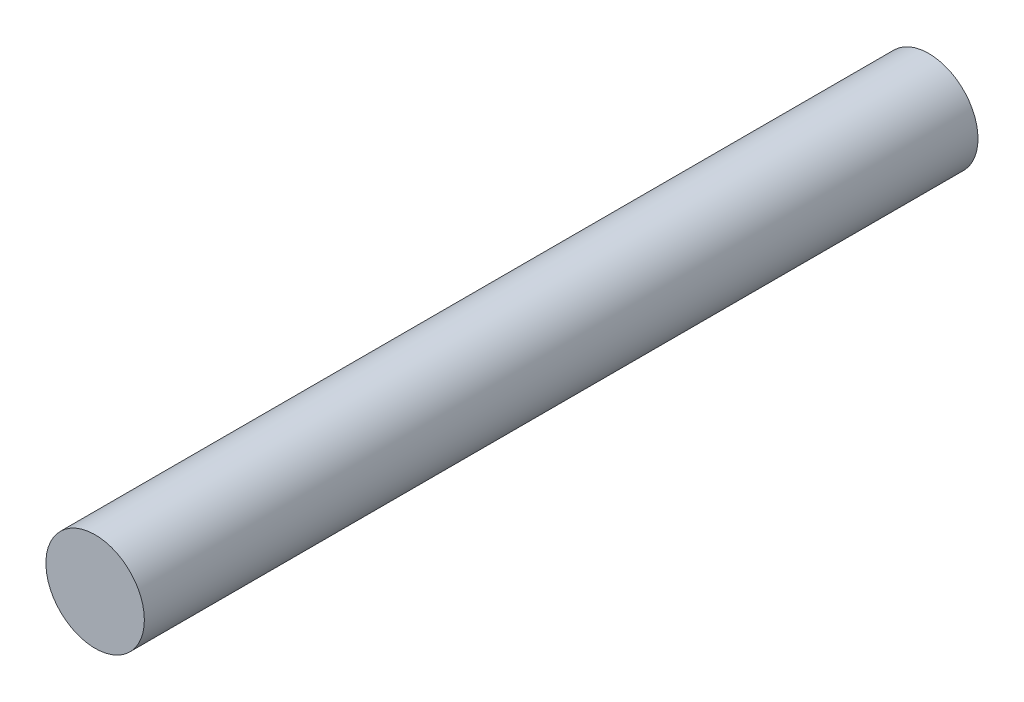
SolidWorks part; units mm, degrees
ref_plane "Front" through (0, 0, 0) normal (0, 0, 1) x (1, 0, 0)
ref_plane "Top" through (0, 0, 0) normal (0, 1, 0) x (1, 0, 0)
ref_plane "Right" through (0, 0, 0) normal (1, 0, 0) x (0, 0, -1)
sketch "Sketch1" plane through (0, 0, 0) normal (0, 0, 1) x (1, 0, 0)
  circle A0 centre (0, 0) radius 3
extrude "Boss-Extrude1" add sketch "Sketch1" along normal blind 50.8
sketch "For Drawing" plane through (0, 0, 0) normal (0, 0, 1) x (1, 0, 0)
  circle A0 centre (0, 0) radius 3
  circle A1 centre (0, 0) radius 3 construction
  dimension "Diameter" = 6
sketch "Break Point" plane through (0, 0, 0) normal (1, 0, 0) x (0, 0, -1)
  line L0 (-50.8, 0) -> (-41.8, 0)
  line L1 (-50.8, 3) -> (-50.8, -3) construction
  line L2 (0, 0) -> (-9, 0)
  line L3 (-9, -3) -> (-9, 3) construction
  line L4 (0, 3) -> (-50.8, 3) construction
  line L5 (-41.8, -3) -> (-41.8, 3) construction
  point P12 (-9, 0)
  point P15 (-41.8, 0)
  dimension "D1" = 9
equation "\"D1@Break Point\"=\"Diameter@Sketch1\" * 1.5"
